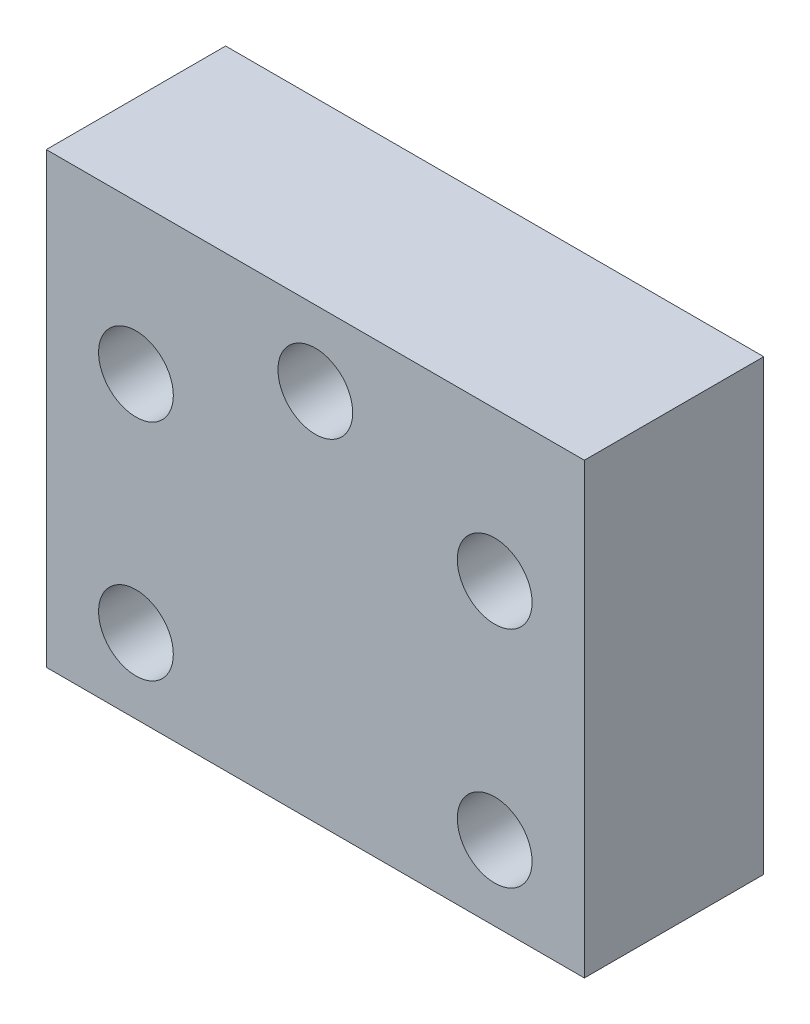
SolidWorks part; units mm, degrees
ref_plane "前视基准面" through (0, 0, 0) normal (0, 0, 1) x (1, 0, 0)
ref_plane "上视基准面" through (0, 0, 0) normal (0, 1, 0) x (1, 0, 0)
ref_plane "右视基准面" through (0, 0, 0) normal (1, 0, 0) x (0, 0, -1)
sketch "草图1" plane through (0, 0, 0) normal (0, 0, 1) x (1, 0, 0)
  line L1 (18, -15) -> (-18, -15)
  line L2 (18, -15) -> (18, 15)
  line L3 (18, 15) -> (-18, 15)
  line L4 (-18, -15) -> (-18, 15)
  line L5 (18, -15) -> (-18, 15) construction
  line L6 (18, 15) -> (-18, -15) construction
  point P0 (0, 0)
  dimension "D1" = 36
  dimension "D2" = 30
extrude "凸台-拉伸1" add sketch "草图1" along normal blind 12
sketch "草图2" plane through (0, 0, 12) normal (0, 0, 1) x (1, 0, 0)
  line L0 (18, 15) -> (-18, 15) construction
  line L1 (18, -15) -> (18, 15) construction
  line L2 (-18, 15) -> (-18, -15) construction
  line L3 (-18, -15) -> (18, -15) construction
  circle A0 centre (-12, 5) radius 2.5
  circle A1 centre (12, 5) radius 2.5
  circle A2 centre (12, -10) radius 2.5
  circle A3 centre (-12, -10) radius 2.5
  point P16 (0, 0)
  dimension "D1" = 5
  dimension "D2" = 5
  dimension "D3" = 5
  dimension "D4" = 5
  dimension "D5" = 10
  dimension "D6" = 5
  dimension "D7" = 10
  dimension "D8" = 5
  dimension "D9" = 6
  dimension "D10" = 6
  dimension "D11" = 6
  dimension "D12" = 6
extrude "切除-拉伸2" cut sketch "草图2" against normal blind 12
sketch "草图3" plane through (0, 0, 12) normal (0, 0, 1) x (1, 0, 0)
  line L0 (18, 15) -> (-18, 15) construction
  circle A0 centre (0, 10) radius 2.5
  dimension "D1" = 5
  dimension "D2" = 5
extrude "切除-拉伸3" cut sketch "草图3" against normal blind 12
